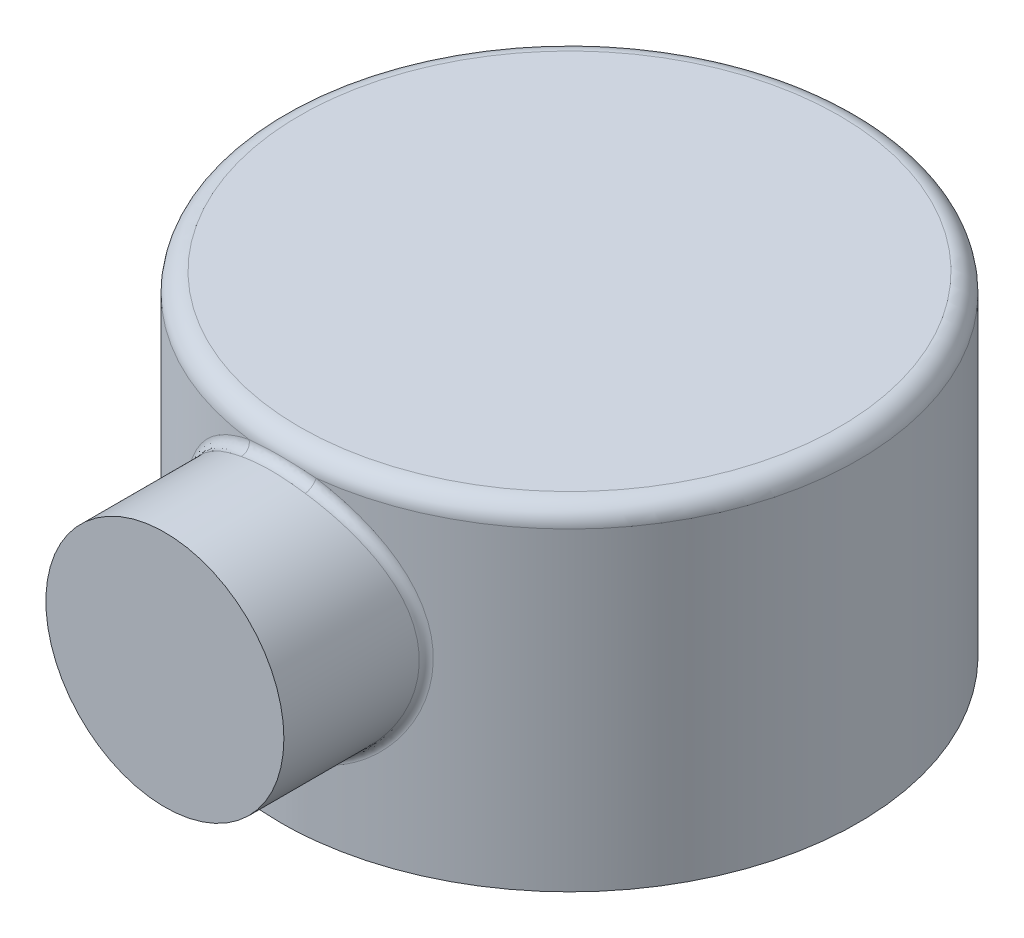
SolidWorks part; units mm, degrees
ref_plane "Front Plane" through (0, 0, 0) normal (0, 0, 1) x (1, 0, 0)
ref_plane "Top Plane" through (0, 0, 0) normal (0, 1, 0) x (1, 0, 0)
ref_plane "Right Plane" through (0, 0, 0) normal (1, 0, 0) x (0, 0, -1)
sketch "Sketch1" plane through (0, 0, 0) normal (0, 1, 0) x (1, 0, 0)
  circle A0 centre (0, 0) radius 60.675
  dimension "D1" = 121.35
extrude "Boss-Extrude1" add sketch "Sketch1" along normal blind 70
sketch "Sketch2" plane through (0, 0, 0) normal (0, 0, 1) x (1, 0, 0)
  line L0 (0, 70) -> (0, 40) construction
  line L1 (60.675, 70) -> (-60.675, 70) construction
  circle A0 centre (0, 40) radius 25
  dimension "D1" = 50
  dimension "D2" = 30
extrude "Boss-Extrude2" add sketch "Sketch2" along normal blind 85
fillet "Fillet1" radius 4 1 edges at (0, 70, 60.675)
fillet "Fillet2" radius 2 1 edges at (24.7446, 43.5642, 55.4)
